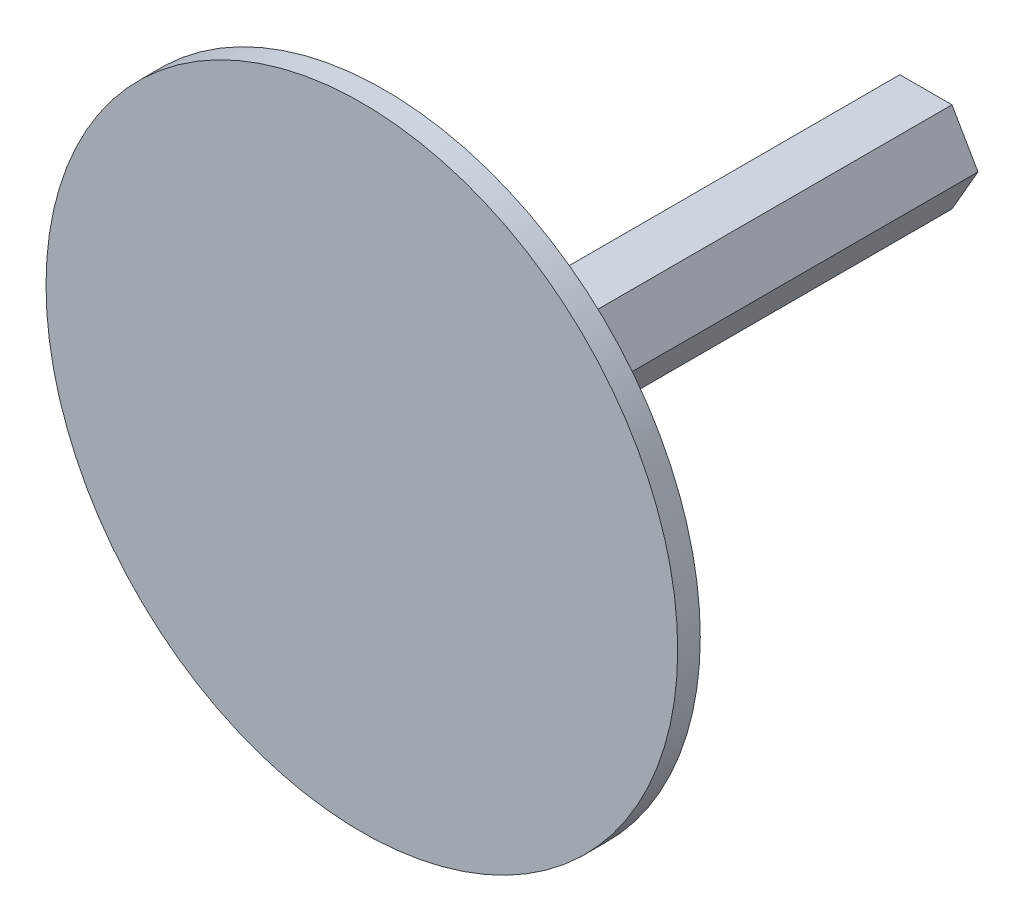
SolidWorks part; units mm, degrees
ref_plane "Front Plane" through (0, 0, 0) normal (0, 0, 1) x (1, 0, 0)
ref_plane "Top Plane" through (0, 0, 0) normal (0, 1, 0) x (1, 0, 0)
ref_plane "Right Plane" through (0, 0, 0) normal (1, 0, 0) x (0, 0, -1)
sketch "Sketch1" plane through (0, 0, 0) normal (0, 0, 1) x (1, 0, 0)
  line L1 (7.3323, 0) -> (3.6662, 6.35)
  line L2 (3.6662, 6.35) -> (-3.6662, 6.35)
  line L3 (-3.6662, 6.35) -> (-7.3323, 0)
  line L4 (-7.3323, 0) -> (-3.6662, -6.35)
  line L5 (-3.6662, -6.35) -> (3.6662, -6.35)
  line L6 (3.6662, -6.35) -> (7.3323, 0)
  circle A0 centre (0, 0) radius 6.35 construction
  dimension "D1" = 12.7
extrude "Boss-Extrude1" add sketch "Sketch1" against normal blind 76.2
sketch "Sketch2" plane through (0, 0, 0) normal (0, 0, 1) x (1, 0, 0)
  circle A0 centre (0, 0) radius 44.45
  dimension "D1" = 88.9
extrude "Boss-Extrude2" add sketch "Sketch2" along normal blind 3.175
